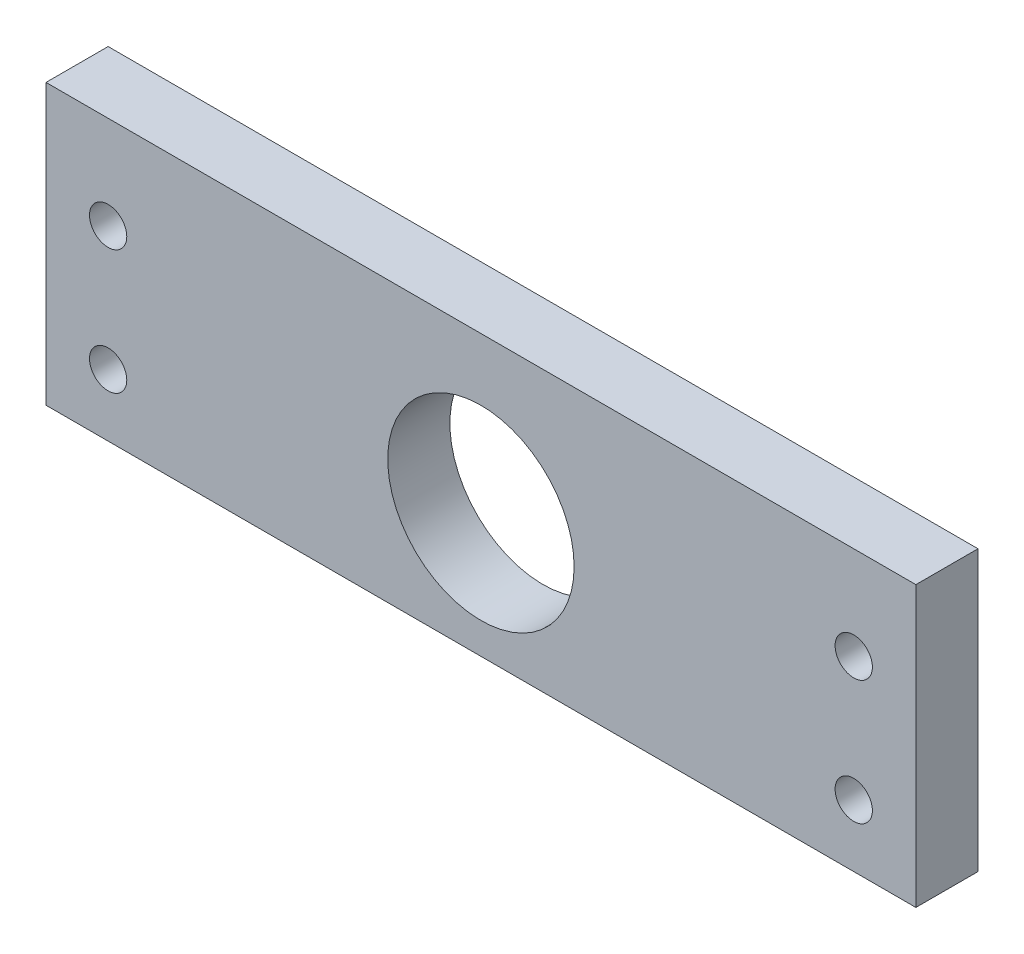
SolidWorks part; units mm, degrees
material "3.0205 (EN AW-1200)"
ref_plane "Plan de face" through (0, 0, 0) normal (0, 0, 1) x (1, 0, 0)
ref_plane "Plan de dessus" through (0, 0, 0) normal (0, 1, 0) x (1, 0, 0)
ref_plane "Plan de droite" through (0, 0, 0) normal (1, 0, 0) x (0, 0, -1)
sketch "Esquisse1" plane through (0, 0, 0) normal (0, 0, 1) x (1, 0, 0)
  line L1 (-35, 12.5) -> (35, 12.5)
  line L2 (-35, 12.5) -> (-35, -10)
  line L3 (-35, -10) -> (35, -10)
  line L4 (35, 12.5) -> (35, -10)
  circle A0 centre (0, 0) radius 7.5
  circle A1 centre (30, -5) radius 1.5
  circle A2 centre (30, 5) radius 1.5
  circle A3 centre (-30, 5) radius 1.5
  circle A4 centre (-30, -5) radius 1.5
  point P0 (0, 0)
  dimension "D3" = 15
  dimension "D6" = 3
  dimension "D1" = 22.5
  dimension "D2" = 70
  dimension "D4" = 12.5
  dimension "D5" = 35
  dimension "D7" = 10
  dimension "D8" = 5
  dimension "D9" = 5
  dimension "D10" = 5
extrude "Boss.-Extru.1" add sketch "Esquisse1" along normal blind 5
